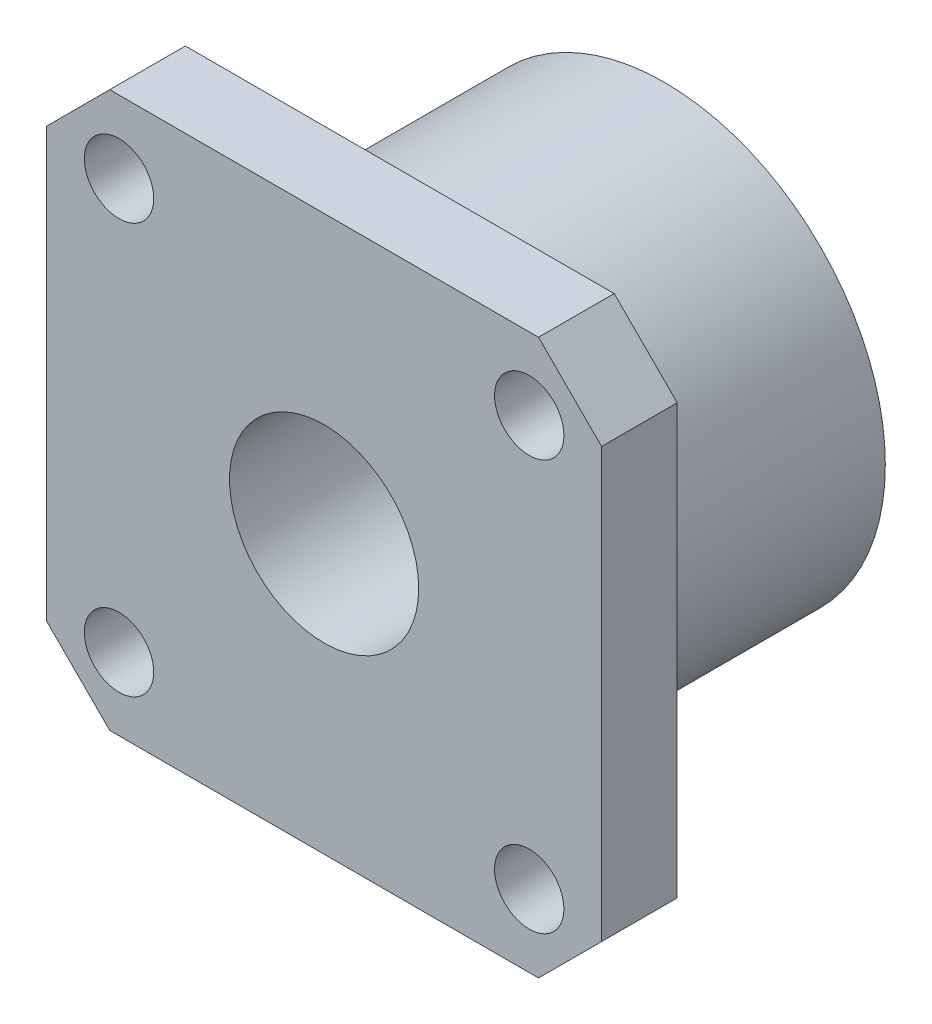
SolidWorks part; units mm, degrees
ref_plane "前视基准面" through (0, 0, 0) normal (0, 0, 1) x (1, 0, 0)
ref_plane "上视基准面" through (0, 0, 0) normal (0, 1, 0) x (1, 0, 0)
ref_plane "右视基准面" through (0, 0, 0) normal (1, 0, 0) x (0, 0, -1)
sketch "草图1" plane through (0, 0, 0) normal (0, 0, 1) x (1, 0, 0)
  line L1 (22, -22) -> (-22, -22)
  line L2 (22, -22) -> (22, 22)
  line L3 (22, 22) -> (-22, 22)
  line L4 (-22, -22) -> (-22, 22)
  line L5 (22, -22) -> (-22, 22) construction
  line L6 (22, 22) -> (-22, -22) construction
  circle A0 centre (-16.2635, 16.2635) radius 2.75
  circle A2 centre (16.2635, 16.2635) radius 2.75
  circle A3 centre (16.2635, -16.2635) radius 2.75
  circle A4 centre (-16.2635, -16.2635) radius 2.75
  point P0 (0, 0)
  dimension "D2" = 5.5
  dimension "D3" = 23
  dimension "D1" = 44
  dimension "D4" = 4
extrude "凸台-拉伸1" add sketch "草图1" along normal blind 6
chamfer "倒角1" distance 5 angle 45 4 edges at (-22, -22, 3) (22, -22, 3) (22, 22, 3) (-22, 22, 3)
sketch "草图2" plane through (0, 0, 0) normal (0, 0, -1) x (-1, 0, 0)
  circle A0 centre (0, 0) radius 17.5
  circle A1 centre (0, 0) radius 7.5
  dimension "D1" = 35
  dimension "D2" = 15
extrude "凸台-拉伸2" add sketch "草图2" along normal blind 21
sketch "草图3" plane through (0, 0, 0) normal (0, 0, -1) x (-1, 0, 0)
  circle A1 centre (0, 0) radius 7.5
  circle A3 centre (0, 0) radius 7.5
  dimension "D1" = 0
extrude "切除-拉伸1" cut sketch "草图3" against normal through all
